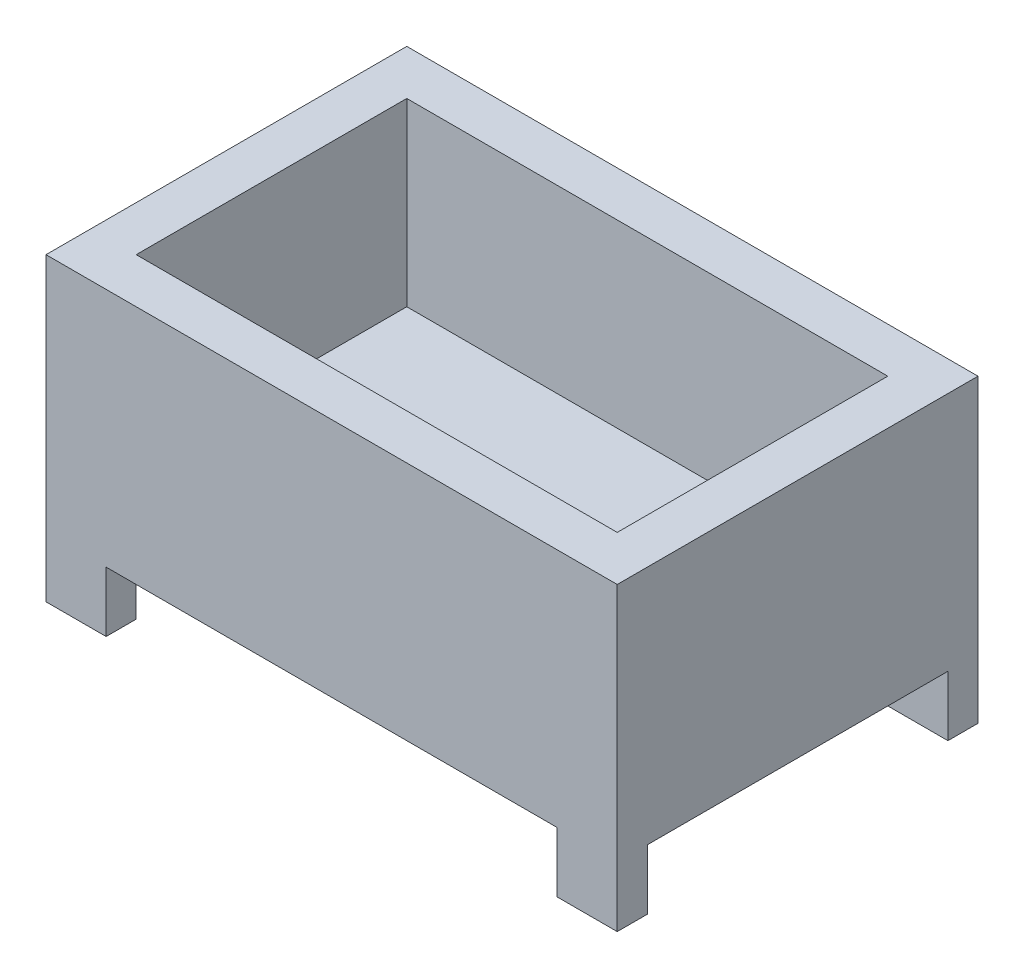
SolidWorks part; units mm, degrees
ref_plane "Plan de face" through (0, 0, 0) normal (0, 0, 1) x (1, 0, 0)
ref_plane "Plan de dessus" through (0, 0, 0) normal (0, 1, 0) x (1, 0, 0)
ref_plane "Plan de droite" through (0, 0, 0) normal (1, 0, 0) x (0, 0, -1)
sketch "Esquisse1" plane through (0, 0, 0) normal (0, 1, 0) x (1, 0, 0)
  line L1 (-19, -12) -> (19, -12)
  line L2 (-19, -12) -> (-19, 12)
  line L3 (-19, 12) -> (19, 12)
  line L4 (19, -12) -> (19, 12)
  dimension "D1" = 12
  dimension "D2" = 24
  dimension "D3" = 38
  dimension "D4" = 19
extrude "Boss.-Extru.1" add sketch "Esquisse1" along normal blind 20
sketch "Esquisse2" plane through (0, 20, 0) normal (0, 1, 0) x (1, 0, 0)
  line L8 (-16, 9) -> (-16, -9)
  line L9 (-16, -9) -> (16, -9)
  line L10 (16, -9) -> (16, 9)
  line L11 (16, 9) -> (-16, 9)
  line L12 (-16, 9) -> (-16, -9)
  line L13 (-16, -9) -> (16, -9)
  line L14 (16, -9) -> (16, 9)
  line L15 (16, 9) -> (-16, 9)
  dimension "D1" = 3
extrude "Enlèv. mat.-Extru.1" cut sketch "Esquisse2" against normal blind 12
sketch "Esquisse3" plane through (0, 0, 12) normal (0, 0, 1) x (1, 0, 0)
  line L0 (-19, 0) -> (19, 0) construction
  line L1 (-15, -1) -> (15, -1)
  line L2 (-15, -1) -> (-15, 4)
  line L3 (-15, 4) -> (15, 4)
  line L4 (15, -1) -> (15, 4)
  point P7 (0, 0)
  dimension "D1" = 15
  dimension "D2" = 30
  dimension "D3" = 4
  dimension "D4" = 1
extrude "Enlèv. mat.-Extru.2" cut sketch "Esquisse3" against normal blind 30
sketch "Esquisse4" plane through (-19, 0, 0) normal (-1, 0, 0) x (0, 0, 1)
  line L0 (-12, 20) -> (-12, 0) construction
  line L1 (-10, -1) -> (10, -1)
  line L2 (-10, -1) -> (-10, 4)
  line L3 (-10, 4) -> (10, 4)
  line L4 (10, -1) -> (10, 4)
  line L5 (-12, 0) -> (12, 0) construction
  dimension "D1" = 20
  dimension "D2" = 2
  dimension "D3" = 4
  dimension "D4" = 1
extrude "Enlèv. mat.-Extru.3" cut sketch "Esquisse4" against normal blind 60
sketch "Esquisse5" plane through (0, 8, 0) normal (0, 1, 0) x (1, 0, 0)
  circle A0 centre (0, 0) radius 2.5
  dimension "D1" = 5
extrude "Enlèv. mat.-Extru.4" cut sketch "Esquisse5" against normal blind 60
